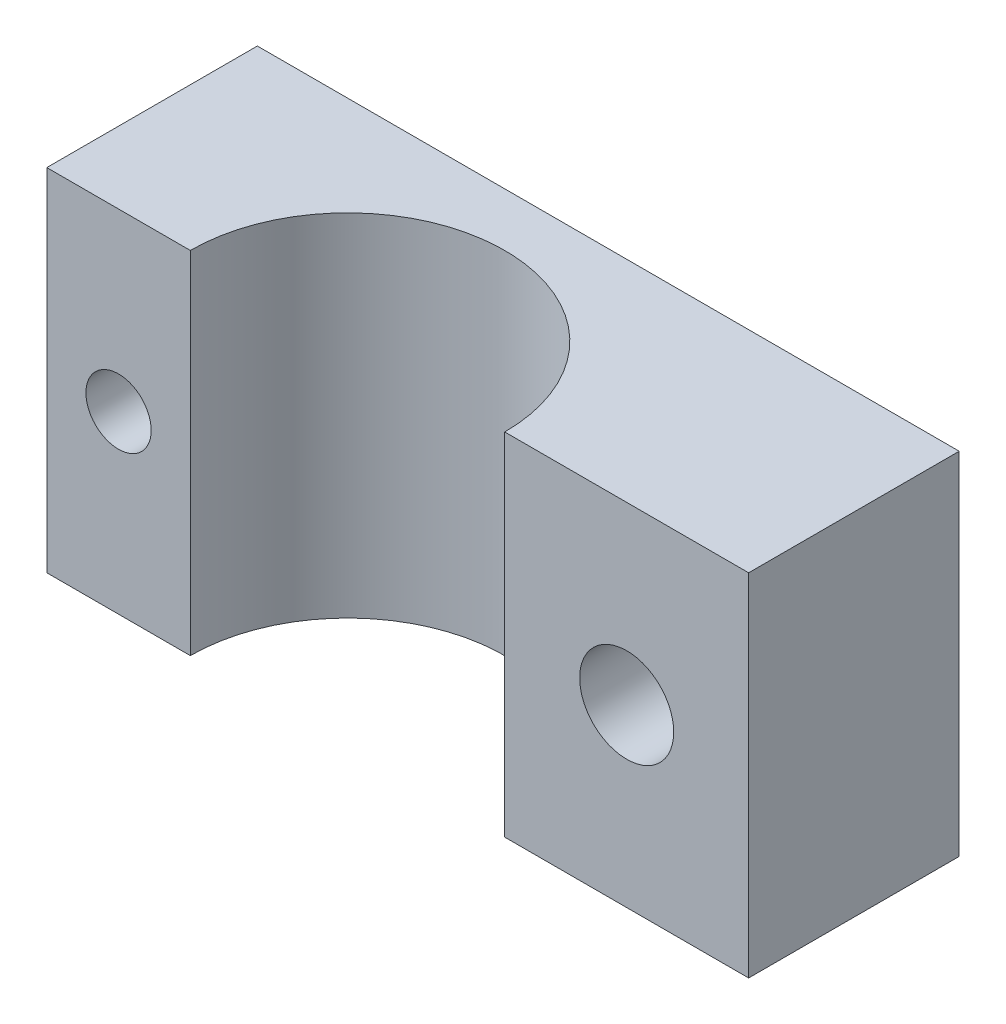
SolidWorks part; units mm, degrees
ref_plane "Front Plane" through (0, 0, 0) normal (0, 0, 1) x (1, 0, 0)
ref_plane "Top Plane" through (0, 0, 0) normal (0, 1, 0) x (1, 0, 0)
ref_plane "Right Plane" through (0, 0, 0) normal (1, 0, 0) x (0, 0, -1)
sketch "Sketch1" plane through (0, 0, 0) normal (0, 1, 0) x (1, 0, 0)
  line L1 (0, 0) -> (50, 0)
  line L2 (0, 0) -> (0, 15)
  line L3 (0, 15) -> (50, 15)
  line L4 (50, 0) -> (50, 15)
  dimension "D1" = 50
  dimension "D2" = 15
extrude "Boss-Extrude1" add sketch "Sketch1" along normal blind 25
sketch "Sketch2" plane through (0, 0, 0) normal (0, 0, 1) x (1, 0, 0)
  line L0 (0, 12.5) -> (21.4235, 12.5) construction
  line L1 (0, 25) -> (0, 0) construction
  line L3 (0, 25) -> (50, 25) construction
  circle A0 centre (21.4235, 25) radius 11.2
  point P8 (0, 0)
  dimension "D2" = 22.4
  dimension "D1" = 21.4235
sketch "Sketch4" plane through (0, 0, 0) normal (0, 1, 0) x (1, 0, 0)
  line L0 (0, 7.5) -> (21.4235, 7.5) construction
  line L1 (0, 15) -> (0, 0) construction
  line L2 (0, 0) -> (21.4235, 0) construction
  circle A0 centre (21.4235, 0) radius 11.2
  point P8 (0, 0)
  dimension "D2" = 22.4
  dimension "D1" = 21.4235
extrude "Cut-Extrude3" cut sketch "Sketch4" along normal through all
sketch "Sketch5" plane through (0, 0, 0) normal (0, 0, 1) x (1, 0, 0)
  line L0 (10.2235, 12.5) -> (0, 12.5) construction
  line L1 (10.2235, 25) -> (10.2235, 0) construction
  line L2 (0, 25) -> (0, 0) construction
  line L3 (32.6235, 12.5) -> (50, 12.5) construction
  line L4 (32.6235, 0) -> (32.6235, 25) construction
  line L5 (50, 25) -> (50, 0) construction
  circle A0 centre (5.1117, 12.5) radius 2.325
  circle A1 centre (41.3117, 12.5) radius 3.35
  dimension "D1" = 4.65
  dimension "D2" = 6.7
extrude "Cut-Extrude4" cut sketch "Sketch5" against normal through all
